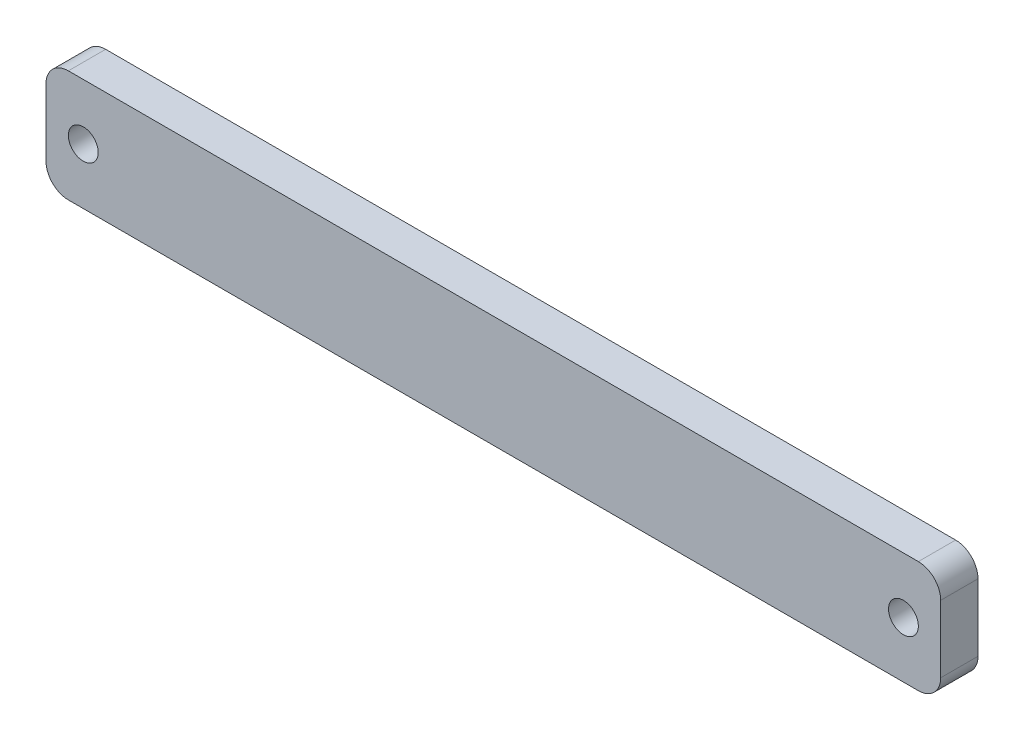
SolidWorks part; units mm, degrees
ref_plane "Plan de face" through (0, 0, 0) normal (0, 0, 1) x (1, 0, 0)
ref_plane "Plan de dessus" through (0, 0, 0) normal (0, 1, 0) x (1, 0, 0)
ref_plane "Plan de droite" through (0, 0, 0) normal (1, 0, 0) x (0, 0, -1)
sketch "Esquisse1" plane through (0, 0, 0) normal (0, 0, 1) x (1, 0, 0)
  line L0 (0, 15.9063) -> (0, -21.3048) construction
  line L1 (-60, 7.5) -> (60, 7.5)
  line L2 (-60, 7.5) -> (-60, -7.5)
  line L3 (-60, -7.5) -> (60, -7.5)
  line L4 (60, 7.5) -> (60, -7.5)
  line L5 (-60, 7.5) -> (60, -7.5) construction
  line L6 (-60, -7.5) -> (60, 7.5) construction
  circle A0 centre (-55, 0) radius 2
  circle A1 centre (55, 0) radius 2
  point P0 (0, 0)
  dimension "D3" = 4
  dimension "D1" = 120
  dimension "D2" = 15
  dimension "D4" = 5
  dimension "D5" = 7.5
extrude "Boss.-Extru.1" add sketch "Esquisse1" along normal blind 5
fillet "Congé1" radius 3 4 edges at (-60, 7.5, 2.5) (-60, -7.5, 2.5) (60, -7.5, 2.5) (60, 7.5, 2.5)
